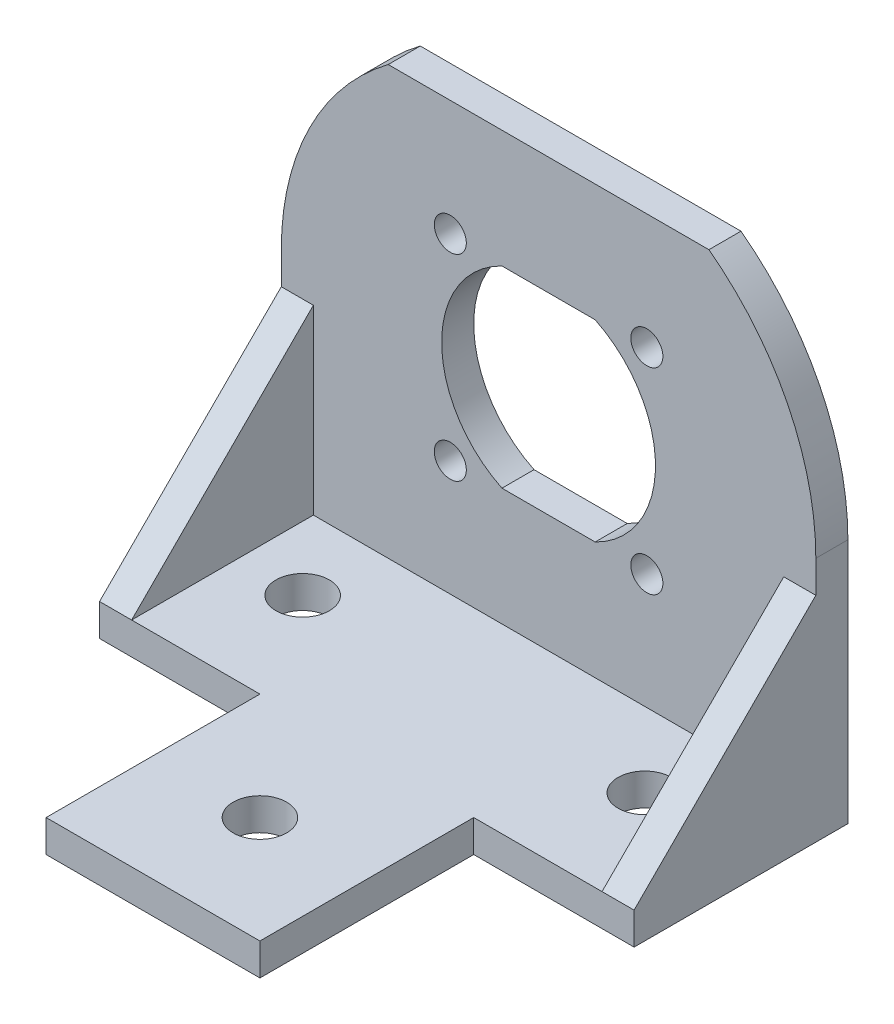
SolidWorks part; units mm, degrees
material "1060 Alloy"
ref_plane "Front Plane" through (0, 0, 0) normal (0, 0, 1) x (1, 0, 0)
ref_plane "Top Plane" through (0, 0, 0) normal (0, 1, 0) x (1, 0, 0)
ref_plane "Right Plane" through (0, 0, 0) normal (1, 0, 0) x (0, 0, -1)
sketch "Sketch1" plane through (0, 0, 0) normal (0, 1, 0) x (1, 0, 0)
  line L1 (-25, 10) -> (25, 10)
  line L2 (-25, 10) -> (-25, -10)
  line L3 (-25, -10) -> (25, -10)
  line L4 (25, 10) -> (25, -10)
  line L5 (-25, 10) -> (25, -10) construction
  line L6 (-25, -10) -> (25, 10) construction
  point P0 (0, 0)
  dimension "D1" = 20
  dimension "D2" = 50
extrude "Boss-Extrude1" add sketch "Sketch1" along normal blind 3
sketch "Sketch2" plane through (0, 3, 0) normal (0, 1, 0) x (1, 0, 0)
  line L0 (25, -10) -> (25, 10) construction
  line L1 (-25, 10) -> (25, 10)
  line L2 (-25, 10) -> (-25, 7)
  line L3 (-25, 7) -> (25, 7)
  line L4 (25, 10) -> (25, 7)
  dimension "D1" = 3
extrude "Boss-Extrude2" add sketch "Sketch2" along normal blind 40
sketch "Sketch6" plane through (0, 3, 0) normal (0, 1, 0) x (1, 0, 0)
  line L5 (-25, 7) -> (-25, -10) construction
  line L7 (25, -10) -> (25, 7) construction
  line L9 (-25, -10) -> (25, -10) construction
  circle A0 centre (-16, 0) radius 2.5
  circle A1 centre (16, 0) radius 2.5
  dimension "D1" = 5
  dimension "D2" = 5
  dimension "D3" = 9
  dimension "D4" = 9
  dimension "D5" = 10
  dimension "D6" = 10
extrude "Cut-Extrude4" cut sketch "Sketch6" against normal up to next
sketch "Sketch7" plane through (-25, 0, 0) normal (-1, 0, 0) x (0, 0, 1)
  line L0 (-7, 3) -> (10, 3)
  line L1 (10, 3) -> (-7, 20)
  line L2 (-7, 43) -> (-7, 3) construction
  line L3 (-7, 20) -> (-7, 3)
extrude "Boss-Extrude3" add sketch "Sketch7" against normal blind 3
sketch "Sketch8" plane through (25, 0, 0) normal (1, 0, 0) x (0, 0, -1)
  line L0 (7, 3) -> (-10, 3)
  line L1 (-10, 3) -> (7, 20)
  line L2 (7, 20) -> (7, 3)
extrude "Boss-Extrude4" add sketch "Sketch8" against normal blind 3
sketch "Sketch9" plane through (0, 0, 10) normal (0, 0, 1) x (1, 0, 0)
  line L0 (25, 3) -> (25, 0) construction
  line L1 (-10, 3) -> (10, 3)
  line L3 (-22, 3) -> (22, 3) construction
  line L4 (-10, 3) -> (-10, 0)
  line L5 (-25, 0) -> (25, 0) construction
  line L6 (-10, 0) -> (10, 0)
  line L7 (10, 0) -> (10, 3)
  line L8 (-25, 3) -> (-25, 0) construction
  point P5 (0.2034, 2.5)
  dimension "D1" = 15
  dimension "D2" = 15
extrude "Boss-Extrude5" add sketch "Sketch9" along normal blind 20
sketch "Sketch10" plane through (0, 3, 0) normal (0, 1, 0) x (1, 0, 0)
  line L4 (10, -30) -> (-10, -30) construction
  line L5 (-10, -30) -> (-10, -10) construction
  circle A1 centre (0, -20) radius 2.5
  dimension "D1" = 5
  dimension "D3" = 10
  dimension "D2" = 10
extrude "Cut-Extrude5" cut sketch "Sketch10" against normal up to next
sketch "Sketch11" plane through (0, 0, -7) normal (0, 0, 1) x (1, 0, 0)
  line L0 (-25, 43) -> (25, 43) construction
  line L1 (-25, 43) -> (-25, 20) construction
  line L2 (25, 43) -> (25, 20) construction
  line L3 (15, 43) -> (25, 43)
  line L4 (25, 43) -> (25, 23)
  line L5 (-15, 43) -> (-25, 43)
  line L6 (-25, 43) -> (-25, 23)
  line L7 (-4.3589, 32) -> (4.3589, 32)
  line L8 (0, 32) -> (0, 23) construction
  line L9 (0, 23) -> (9.8489, 23) construction
  line L10 (-4.3589, 14) -> (4.3589, 14)
  circle A6 centre (9.1924, 32.1924) radius 1.5
  circle A7 centre (9.1924, 13.8076) radius 1.5
  circle A8 centre (-9.1924, 13.8076) radius 1.5
  circle A9 centre (-9.1924, 32.1924) radius 1.5
  arc A11 (-25, 23) -> (-15, 43) centre (0, 23) cw
  arc A12 (25, 23) -> (15, 43) centre (0, 23) ccw
  arc A13 (4.3589, 32) -> (4.3589, 14) centre (0, 23) cw
  arc A14 (-4.3589, 32) -> (-4.3589, 14) centre (0, 23) ccw
  point P13 (0, 23)
  dimension "D1" = 4
  dimension "D7" = 3
  dimension "D10" = 10
  dimension "D8" = 25
  dimension "D9" = 9
  dimension "D2" = 20
  dimension "D3" = 25
  dimension "D4" = 13
  dimension "D5" = 13
  dimension "D6" = 13
extrude "Cut-Extrude6" cut sketch "Sketch11" against normal up to surface (3 mm away) up to face at (0, 21.5, -10)
